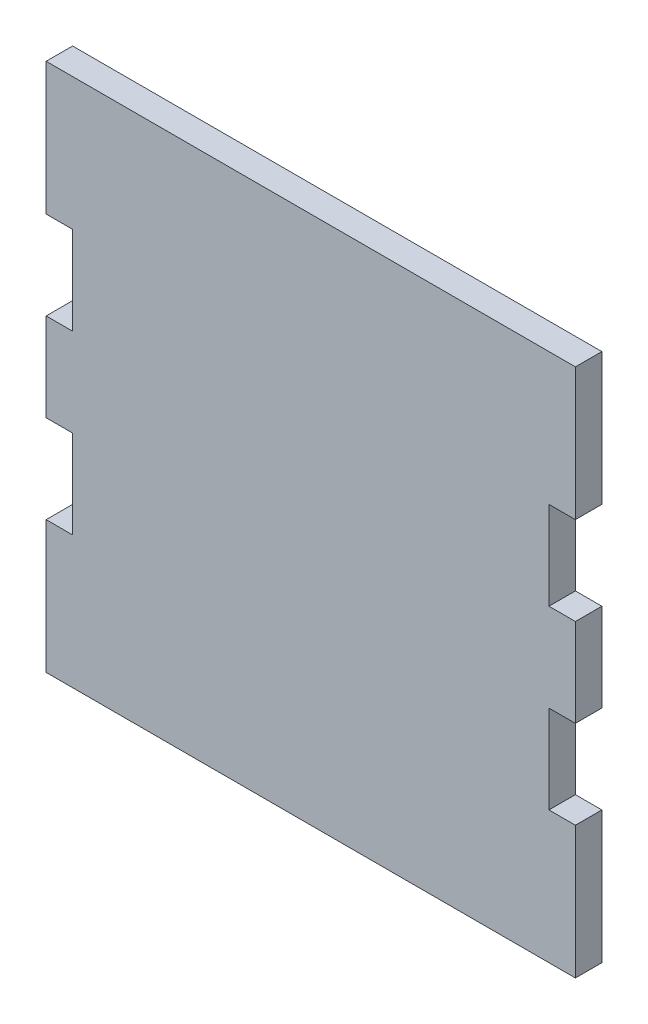
SolidWorks part; units mm, degrees
ref_plane "Plan de face" through (0, 0, 0) normal (0, 0, 1) x (1, 0, 0)
ref_plane "Plan de dessus" through (0, 0, 0) normal (0, 1, 0) x (1, 0, 0)
ref_plane "Plan de droite" through (0, 0, 0) normal (1, 0, 0) x (0, 0, -1)
sketch "Sketch1" plane through (0, 0, 0) normal (0, 0, 1) x (1, 0, 0)
  line L0 (30, 30) -> (30, 15)
  line L1 (-30, -30) -> (30, -30)
  line L2 (-30, -30) -> (-30, 30)
  line L3 (-30, 30) -> (30, 30)
  line L4 (30, -30) -> (30, 30)
  line L5 (27, 15) -> (27, 5)
  line L6 (27, -5) -> (27, -15)
  line L7 (30, 30) -> (27, 30)
  line L8 (30, 15) -> (27, 15)
  line L10 (30, 5) -> (30, -5)
  line L11 (30, 5) -> (27, 5)
  line L12 (30, -5) -> (27, -5)
  line L14 (30, -30) -> (30, -15)
  line L15 (30, -30) -> (27, -30)
  line L16 (30, -15) -> (27, -15)
  line L19 (0, -55) -> (0, 55) construction
  line L20 (-30, -15) -> (-27, -15)
  line L21 (-27, -5) -> (-27, -15)
  line L22 (-30, -5) -> (-27, -5)
  line L23 (-30, 5) -> (-27, 5)
  line L24 (-27, 15) -> (-27, 5)
  line L25 (-30, 15) -> (-27, 15)
  point P0 (0, 0)
  dimension "D1" = 60
  dimension "D2" = 60
  dimension "D3" = 3
  dimension "D4" = 3
  dimension "D5" = 3
  dimension "D6" = 15
  dimension "D7" = 10
  dimension "D8" = 15
  dimension "D9" = 10
  dimension "D10" = 10
extrude "Boss-Extrude1" add sketch "Sketch1" along normal blind 3
